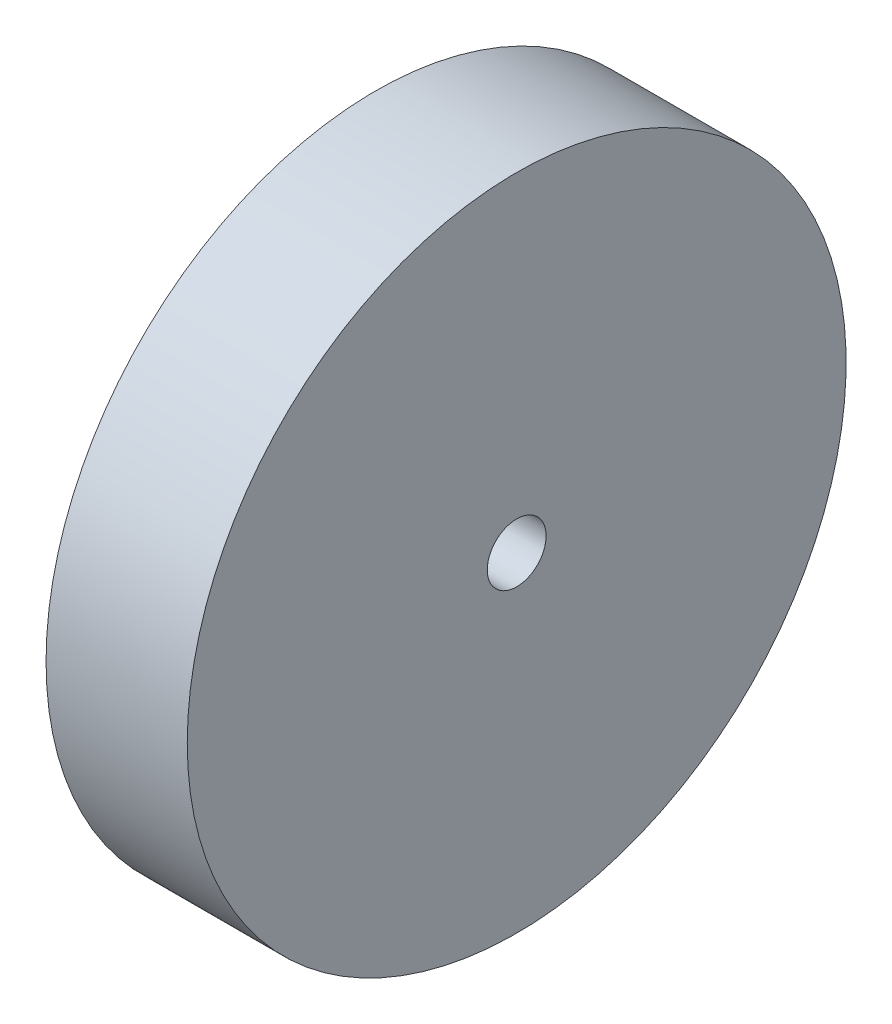
SolidWorks part; units mm, degrees
ref_plane "前视基准面" through (0, 0, 0) normal (0, 0, 1) x (1, 0, 0)
ref_plane "上视基准面" through (0, 0, 0) normal (0, 1, 0) x (1, 0, 0)
ref_plane "右视基准面" through (0, 0, 0) normal (1, 0, 0) x (0, 0, -1)
sketch "草图1" plane through (0, 0, 0) normal (0, 0, 1) x (1, 0, 0)
  line L0 (-16.7109, 0) -> (33.0699, 0) construction
  line L1 (-6, 0) -> (6, 0)
  line L2 (-6, 0) -> (-6, -28)
  line L3 (-6, -28) -> (6, -28)
  line L4 (6, 0) -> (6, -28)
  point P4 (0, 0)
  dimension "D1" = 12
  dimension "D2" = 28
revolve "旋转1" add sketch "草图1" angle 360 about L0
sketch "草图2" plane through (-6, 0, 0) normal (-1, 0, 0) x (0, 0, 1)
  circle A0 centre (0, 0) radius 2.5
  dimension "D1" = 5
extrude "切除-拉伸1" cut sketch "草图2" against normal through all
